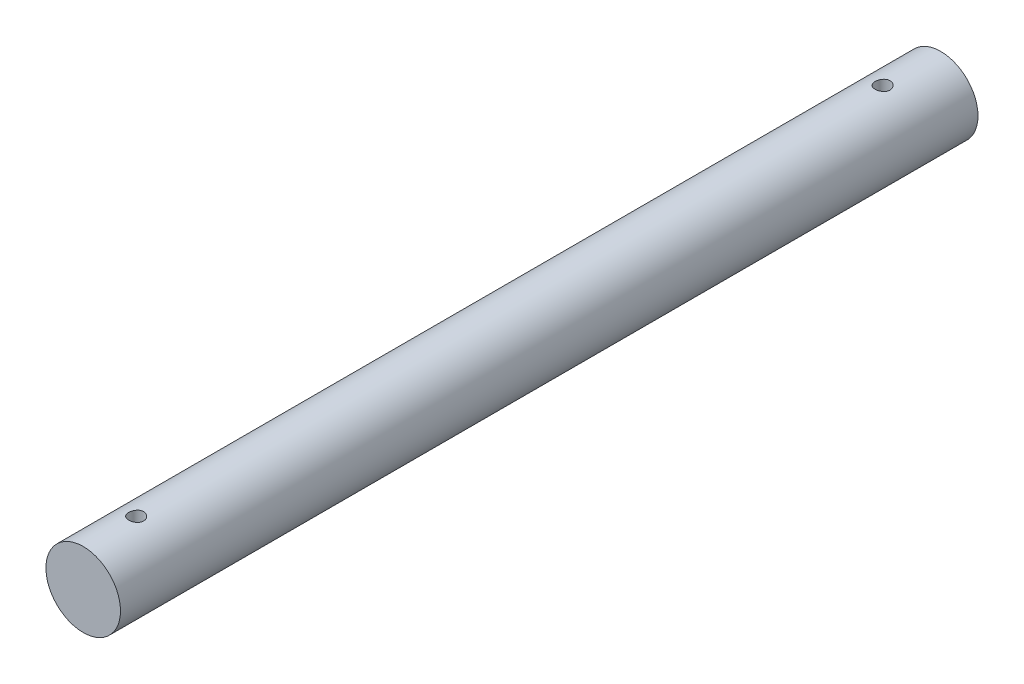
SolidWorks part; units mm, degrees
ref_plane "Спереди" through (0, 0, 0) normal (0, 0, 1) x (1, 0, 0)
ref_plane "Сверху" through (0, 0, 0) normal (0, 1, 0) x (1, 0, 0)
ref_plane "Справа" through (0, 0, 0) normal (1, 0, 0) x (0, 0, -1)
sketch "Эскиз1" plane through (0, 0, 0) normal (0, 0, 1) x (1, 0, 0)
  circle A0 centre (0, 0) radius 5
extrude "Вытянуть1" add sketch "Эскиз1" along normal blind 115
sketch "Эскиз2" plane through (0, 0, 0) normal (0, 1, 0) x (1, 0, 0)
  circle A0 centre (0, -7.8013) radius 1
extrude "Вырез-Вытянуть1" cut sketch "Эскиз2" against normal mid plane 20
sketch "Эскиз4" plane through (0, 0, 0) normal (0, 1, 0) x (1, 0, 0)
  circle A0 centre (0, -107.8985) radius 1
extrude "Вырез-Вытянуть2" cut sketch "Эскиз4" against normal mid plane 20
